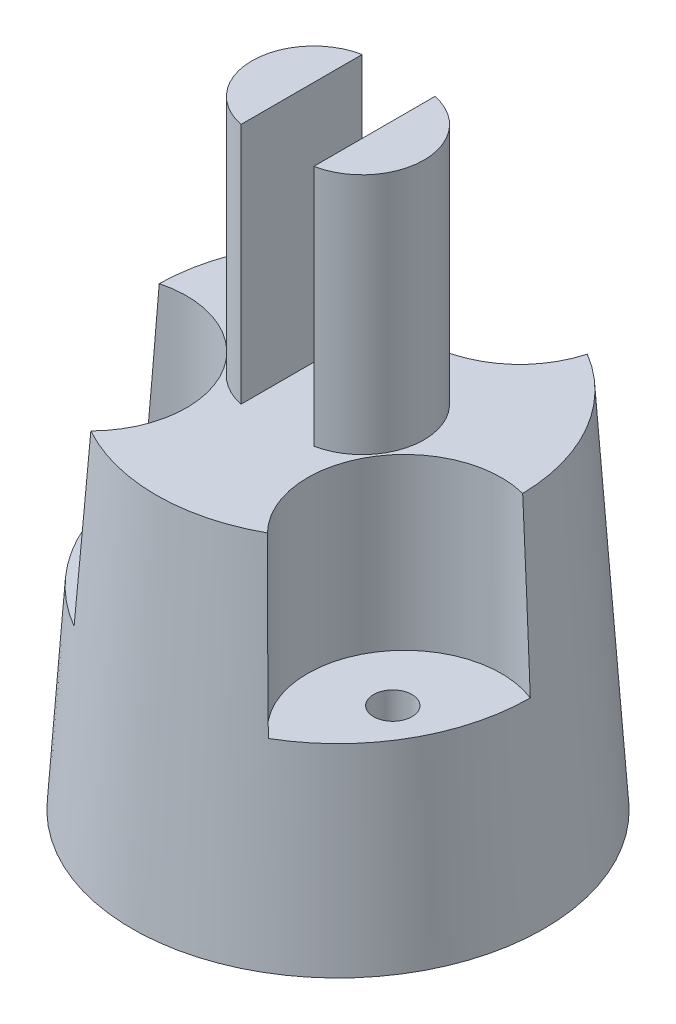
SolidWorks part; units mm, degrees
ref_plane "Front Plane" through (0, 0, 0) normal (0, 0, 1) x (1, 0, 0)
ref_plane "Top Plane" through (0, 0, 0) normal (0, 1, 0) x (1, 0, 0)
ref_plane "Right Plane" through (0, 0, 0) normal (1, 0, 0) x (0, 0, -1)
sketch "Sketch1" plane through (0, 0, 0) normal (0, 0, 1) x (1, 0, 0)
  line L0 (0, 0) -> (8.496, 0)
  line L4 (0, 15) -> (0, 0)
  line L5 (8.496, 0) -> (7.5, 15)
  line L6 (7.5, 15) -> (3.5, 15)
  line L7 (3.5, 15) -> (0, 15)
  dimension "D1" = 8.496
  dimension "D4" = 15
  dimension "D6" = 4
revolve "Revolve1" add sketch "Sketch1" angle 360 about L4
sketch "Sketch5" plane through (0, 0, 0) normal (0, -1, 0) x (1, 0, 0)
  circle A1 centre (5.4016, 3.1409) radius 0.7937
  circle A3 centre (0.0194, -6.2484) radius 0.7938
  circle A4 centre (-5.4209, 3.1074) radius 0.7937
  dimension "D7" = 1.5875
  dimension "D8" = 1.5875
  dimension "D9" = 1.5875
  dimension "D1" = 6.2484
  dimension "D2" = 5.3822
  dimension "D3" = 5.4016
  dimension "D4" = 5.4209
  dimension "D5" = 3.1074
  dimension "D6" = 3.1409
extrude "Cut-Extrude4" cut sketch "Sketch5" against normal up to next
sketch "Sketch4" plane through (0, 15, 0) normal (0, 1, 0) x (1, 0, 0)
  line L0 (0, 0) -> (0, 7.5) construction
  line L1 (0, 0) -> (6.4952, -3.75) construction
  line L2 (0, 0) -> (-6.4952, -3.75) construction
  circle A0 centre (0, 0) radius 7.5 construction
  circle A1 centre (0, 7.5) radius 4
  circle A2 centre (6.4952, -3.75) radius 4
  circle A3 centre (-6.4952, -3.75) radius 4
  circle A4 centre (5.4016, -3.1409) radius 0.7937 construction
  circle A5 centre (-5.4209, -3.1074) radius 0.7937 construction
  dimension "D1" = 8
  dimension "D2" = 8
  dimension "D3" = 8
  dimension "D4" = 1.2518
  dimension "D5" = 1.2518
extrude "Cut-Extrude3" cut sketch "Sketch4" against normal blind 7
sketch "Sketch8" plane through (0, 15, 0) normal (0, 1, 0) x (1, 0, 0)
  line L2 (1.5, 2.5) -> (1.5, -2.5)
  line L8 (-1.5, 2.5) -> (-1.5, -2.5)
  arc A0 (-1.5, -2.5) -> (-1.5, 2.5) centre (-1, 0) cw
  arc A1 (1.5, -2.5) -> (1.5, 2.5) centre (1, 0) ccw
  dimension "D5" = 1
  dimension "D6" = 1
  dimension "D1" = 3
  dimension "D2" = 5
  dimension "D3" = 1.5
  dimension "D4" = 5
  dimension "D8" = 0
extrude "Boss-Extrude1" add sketch "Sketch8" along normal blind 10
